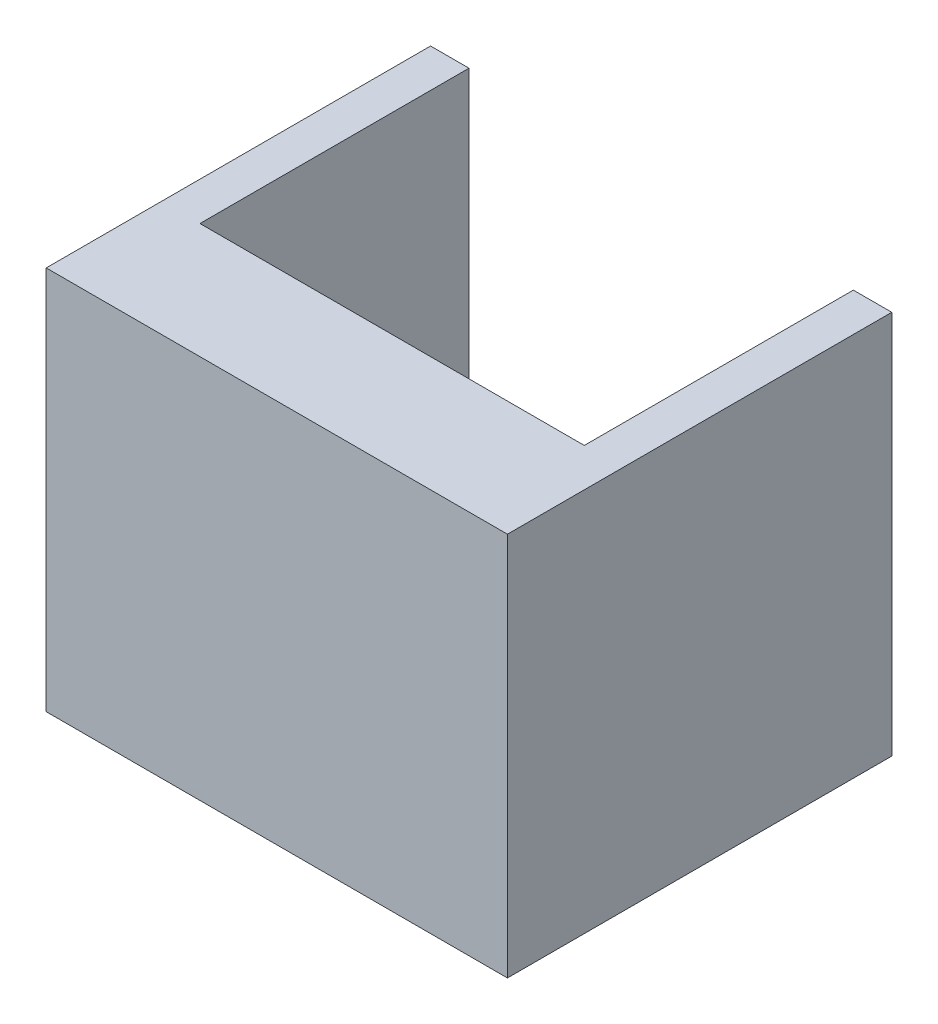
SolidWorks part; units mm, degrees
ref_plane "Front Plane" through (0, 0, 0) normal (0, 0, 1) x (1, 0, 0)
ref_plane "Top Plane" through (0, 0, 0) normal (0, 1, 0) x (1, 0, 0)
ref_plane "Right Plane" through (0, 0, 0) normal (1, 0, 0) x (0, 0, -1)
sketch "Sketch1" plane through (0, 0, 0) normal (0, 1, 0) x (1, 0, 0)
  line L0 (14.6, 5.1113) -> (15.6, 5.1113)
  line L1 (3.6, 5.1113) -> (4.6, 5.1113)
  line L2 (3.6, 5.1113) -> (3.6, -4.8887)
  line L3 (3.6, -4.8887) -> (15.6, -4.8887)
  line L4 (15.6, 5.1113) -> (15.6, -4.8887)
  line L6 (4.6, 5.1113) -> (4.6, -1.8887)
  line L7 (4.6, -1.8887) -> (14.6, -1.8887)
  line L8 (14.6, 5.1113) -> (14.6, -1.8887)
  dimension "D1" = 3
  dimension "D2" = 1
  dimension "D3" = 1
  dimension "D4" = 10
  dimension "D5" = 7
extrude "Boss-Extrude1" add sketch "Sketch1" along normal blind 10
